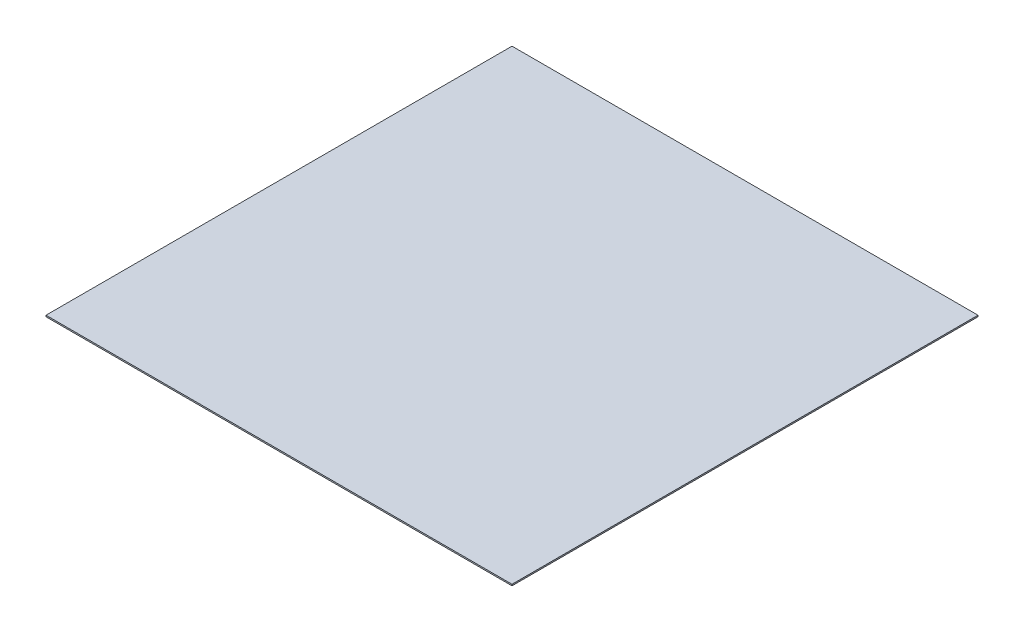
SolidWorks part; units mm, degrees
ref_plane "Front Plane" through (0, 0, 0) normal (0, 0, 1) x (1, 0, 0)
ref_plane "Top Plane" through (0, 0, 0) normal (0, 1, 0) x (1, 0, 0)
ref_plane "Right Plane" through (0, 0, 0) normal (1, 0, 0) x (0, 0, -1)
sketch "Sketch1" plane through (0, 0, 0) normal (0, 1, 0) x (1, 0, 0)
  line L1 (0, 0) -> (1000, 0)
  line L2 (0, 0) -> (0, 1000)
  line L3 (0, 1000) -> (1000, 1000)
  line L4 (1000, 0) -> (1000, 1000)
  dimension "D1" = 1000
  dimension "D2" = 1000
extrude "Boss-Extrude1" add sketch "Sketch1" along normal blind 3
